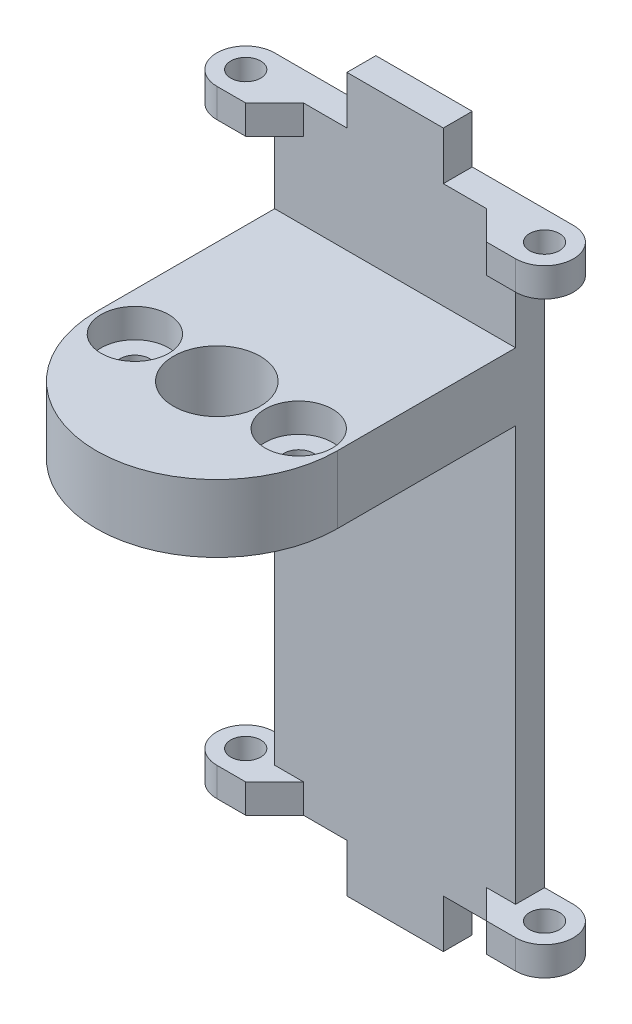
SolidWorks part; units mm, degrees
ref_plane "Front Plane" through (0, 0, 0) normal (0, 0, 1) x (1, 0, 0)
ref_plane "Top Plane" through (0, 0, 0) normal (0, 1, 0) x (1, 0, 0)
ref_plane "Right Plane" through (0, 0, 0) normal (1, 0, 0) x (0, 0, -1)
sketch "Sketch11" plane through (0, 0, 51.65) normal (0, -1, 0) x (1, 0, 0)
  line L0 (12.5, 90) -> (12.5, 71.5)
  line L1 (-12.5, 90) -> (-12.5, 71.5)
  line L6 (-12.5, 71.5) -> (12.5, 71.5)
  circle A0 centre (-8.5, 90) radius 1.55
  circle A1 centre (8.5, 90) radius 1.55
  circle A4 centre (0, 90) radius 4.5
  arc A5 (-12.5, 90) -> (12.5, 90) centre (0, 90) cw
extrude "Boss-Extrude1" add sketch "Sketch11" along normal blind 7
sketch "Sketch12" plane through (0, 0, 123.15) normal (0, 0, -1) x (-1, 0, 0)
  line L0 (-12.5, 0) -> (-12.5, 11)
  line L1 (12.5, 0) -> (12.5, 11)
  line L3 (-12.5, 0) -> (-12.5, -7)
  line L4 (-12.5, -7) -> (-12.5, -53)
  line L5 (12.5, 0) -> (12.5, -7)
  line L6 (12.5, -7) -> (12.5, -53)
  line L8 (-12.5, 11) -> (-5, 11)
  line L9 (-5, 11) -> (-5, 16)
  line L12 (5, 11) -> (12.5, 11)
  line L13 (-5, 16) -> (5, 16)
  line L14 (5, 16) -> (5, 11)
  line L15 (-12.5, -53) -> (-5, -53)
  line L16 (-5, -53) -> (-5, -58)
  line L17 (-5, -58) -> (5, -58)
  line L18 (5, -58) -> (5, -53)
  line L19 (5, -53) -> (12.5, -53)
extrude "Boss-Extrude2" add sketch "Sketch12" along normal blind 3
sketch "Sketch13" plane through (0, 0, 0) normal (0, 1, 0) x (1, 0, 0)
  circle A0 centre (-8.5, -141.65) radius 3.5
  circle A1 centre (8.5, -141.65) radius 3.5
extrude "Cut-Extrude1" cut sketch "Sketch13" against normal blind 3
ref_plane "Plane1" through (0, 11, 0) normal (0, 1, 0) x (1, 0, 0)
sketch "Sketch14" plane through (0, 11, 0) normal (0, 1, 0) x (1, 0, 0)
  line L0 (12.5, -123.15) -> (15.5, -123.15) construction
  line L1 (-12.5, -141.65) -> (-12.5, -123.15) construction
  line L2 (-12.5, -123.15) -> (-15.5, -123.15) construction
  line L3 (5, -123.15) -> (12.5, -123.15) construction
  line L4 (12.5, -123.15) -> (12.5, -141.65) construction
  line L6 (15.5, -120.15) -> (-15.5, -120.15)
  line L7 (-15.5, -126.15) -> (-12.5, -126.15)
  line L11 (12.5, -126.15) -> (15.5, -126.15)
  line L12 (-12.5, -126.15) -> (-9.5, -123.15)
  line L13 (12.5, -126.15) -> (9.5, -123.15)
  line L15 (-12.5, -123.15) -> (12.5, -123.15) construction
  line L16 (9.5, -123.15) -> (-9.5, -123.15)
  arc A0 (-15.5, -120.15) -> (-15.5, -126.15) centre (-15.5, -123.15) ccw
  circle A1 centre (-15.5, -123.15) radius 1.55
  circle A2 centre (15.5, -123.15) radius 1.55
  arc A3 (15.5, -120.15) -> (15.5, -126.15) centre (15.5, -123.15) cw
extrude "Boss-Extrude3" add sketch "Sketch14" against normal blind 3
ref_plane "Plane2" through (0, -53, 0) normal (0, -1, 0) x (-1, 0, 0)
sketch "Sketch15" plane through (0, -53, 0) normal (0, -1, 0) x (-1, 0, 0)
  line L0 (15.5, -126.15) -> (12.5, -126.15) construction
  line L1 (15.5, -120.15) -> (-15.5, -120.15)
  line L2 (-15.5, -126.15) -> (-12.5, -126.15)
  line L3 (-12.5, -126.15) -> (-9.5, -123.15)
  line L4 (-12.5, -123.15) -> (-5, -123.15) construction
  line L5 (15.5, -126.15) -> (12.5, -126.15)
  line L6 (12.5, -126.15) -> (9.5, -123.15)
  line L7 (5, -123.15) -> (12.5, -123.15) construction
  line L8 (9.5, -123.15) -> (-9.5, -123.15)
  circle A0 centre (15.5, -123.15) radius 1.55
  circle A1 centre (-15.5, -123.15) radius 1.55
  arc A2 (15.5, -120.15) -> (15.5, -126.15) centre (15.5, -123.15) cw
  arc A3 (-15.5, -120.15) -> (-15.5, -126.15) centre (-15.5, -123.15) ccw
  arc A4 (-15.5, -120.15) -> (-15.5, -126.15) centre (-15.5, -123.15) ccw construction
extrude "Boss-Extrude4" add sketch "Sketch15" against normal blind 3
